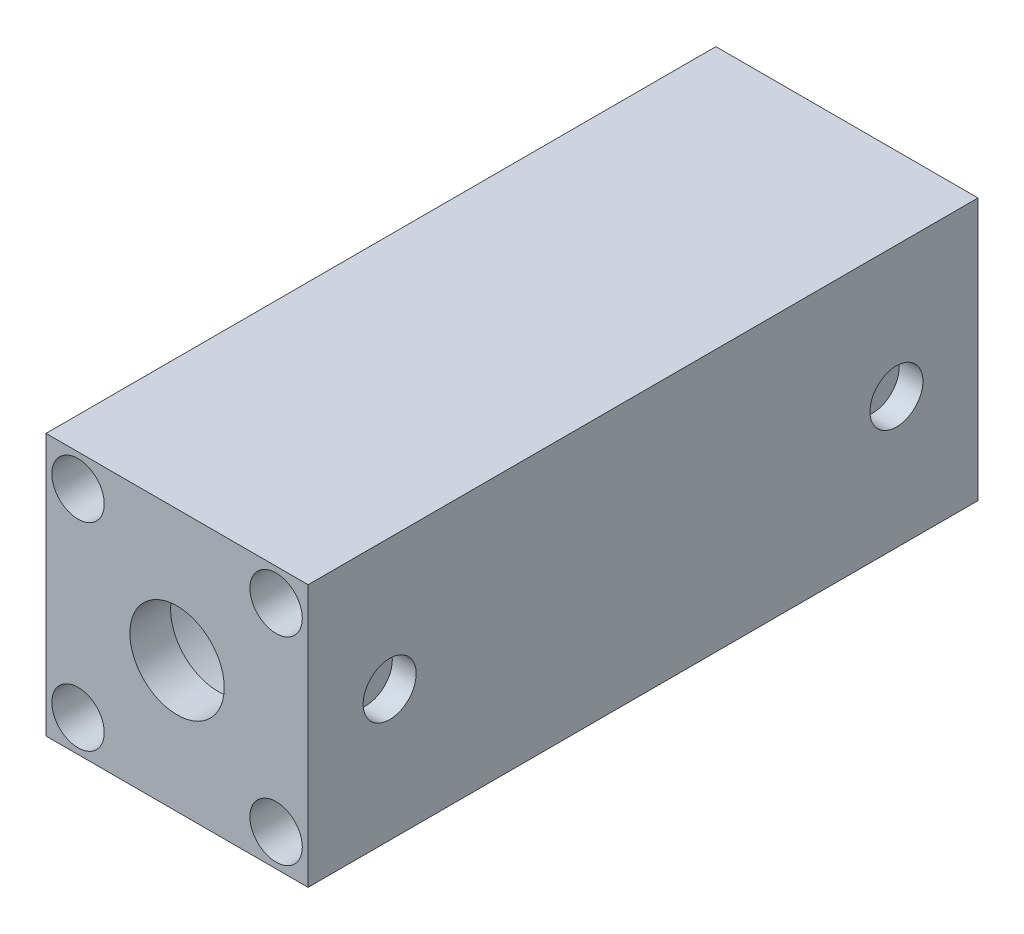
SolidWorks part; units mm, degrees
ref_plane "Front Plane" through (0, 0, 0) normal (0, 0, 1) x (1, 0, 0)
ref_plane "Top Plane" through (0, 0, 0) normal (0, 1, 0) x (1, 0, 0)
ref_plane "Right Plane" through (0, 0, 0) normal (1, 0, 0) x (0, 0, -1)
sketch "Sketch1" plane through (0, 0, 0) normal (0, 0, 1) x (1, 0, 0)
  line L0 (-22.5, -22.5) -> (22.5, -22.5)
  line L1 (22.5, -22.5) -> (22.5, 22.5)
  line L2 (22.5, 22.5) -> (-22.5, 22.5)
  line L3 (-22.5, 22.5) -> (-22.5, -22.5)
  circle A0 centre (-17, -17) radius 2.75
  circle A1 centre (-17, 17) radius 2.75
  circle A2 centre (17, -17) radius 2.75
  circle A3 centre (17, 17) radius 2.75
  circle A4 centre (0, 0) radius 16
extrude "SMC 45 mm square body and four 5.5 mm through holes" add sketch "Sketch1" along normal blind 115
sketch "Sketch2" plane through (0, 0, 0) normal (0, 0, 1) x (1, 0, 0)
  circle A0 centre (0, 0) radius 16
extrude "Head end clearance envelope" add sketch "Sketch2" along normal blind 7
sketch "Sketch3" plane through (0, 0, 0) normal (0, 0, 1) x (1, 0, 0)
  circle A0 centre (0, 0) radius 16
  circle A1 centre (0, 0) radius 8.1
extrude "Rod cover and 16 mm rod clearance" add sketch "Sketch3" along normal blind 7 from offset 108
sketch "Sketch4" plane through (0, 0, 0) normal (0, 0, 1) x (1, 0, 0)
  circle A0 centre (-17, -17) radius 4.5
  circle A1 centre (-17, 17) radius 4.5
  circle A2 centre (17, -17) radius 4.5
  circle A3 centre (17, 17) radius 4.5
extrude "Rear bolt head counterbores" cut sketch "Sketch4" along normal blind 7
sketch "Sketch5" plane through (0, 0, 0) normal (0, 0, 1) x (1, 0, 0)
  circle A0 centre (-17, -17) radius 4.5
  circle A1 centre (-17, 17) radius 4.5
  circle A2 centre (17, -17) radius 4.5
  circle A3 centre (17, 17) radius 4.5
extrude "Front mounting counterbores" cut sketch "Sketch5" along normal blind 7 from offset 108
sketch "Sketch6" plane through (0, 0, 0) normal (1, 0, 0) x (0, 0, -1)
  circle A0 centre (-14, 0) radius 4.55
  circle A1 centre (-101, 0) radius 4.55
extrude "Top Rc 1/8 port clearance for layout" cut sketch "Sketch6" against normal blind 4.1 from offset 22.5
